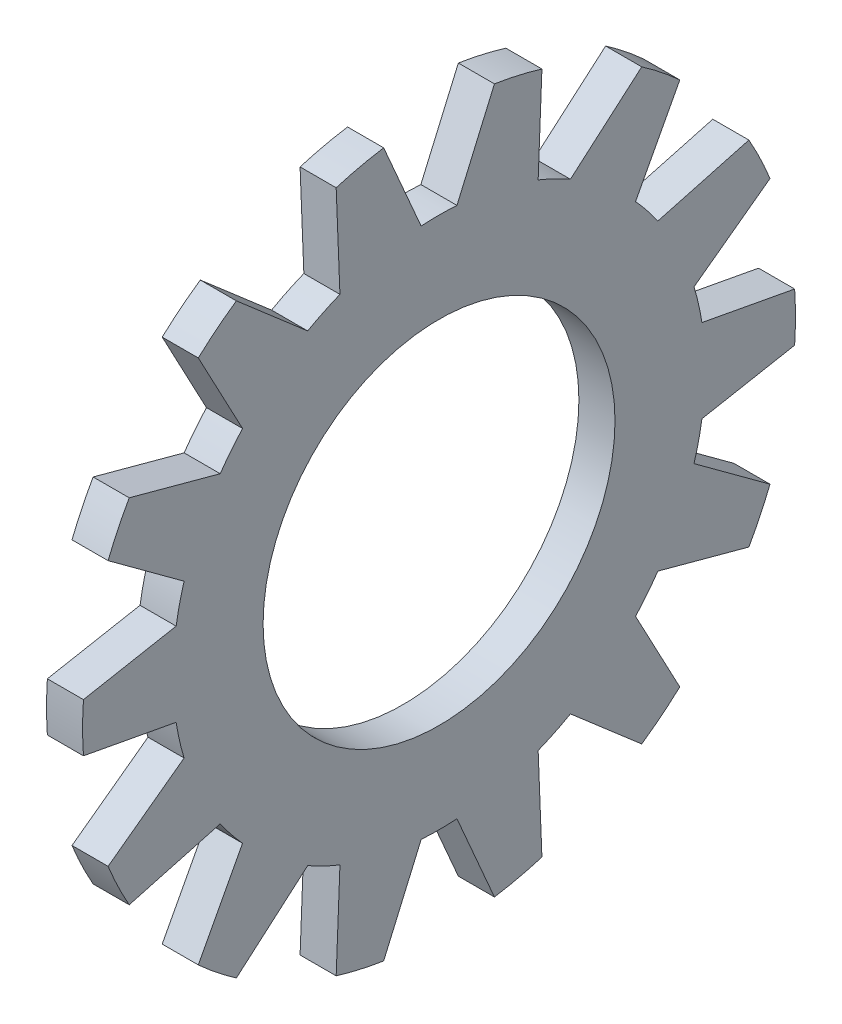
SolidWorks part; units mm, degrees
material "AISI 316 Stainless Steel Sheet (SS)"
ref_plane "Plane1" through (0, 0, 0) normal (0, 0, 1) x (1, 0, 0)
ref_plane "Plane2" through (0, 0, 0) normal (0, 1, 0) x (1, 0, 0)
ref_plane "Plane3" through (0, 0, 0) normal (1, 0, 0) x (0, 0, -1)
sketch "SecSke" plane through (0, 0, 0) normal (0, 0, 1) x (1, 0, 0)
  line L0 (-34.925, 0) -> (9.525, 0) construction
  line L1 (0, 2.4765) -> (0, 5.0165)
  line L2 (0, 5.0165) -> (-0.508, 5.0165)
  line L3 (-0.508, 5.0165) -> (-0.508, 2.4765)
  line L4 (-0.508, 2.4765) -> (0, 2.4765)
  dimension "Thickness" = 0.508
  dimension "Inside_dia" = 4.953
  dimension "Outside_dia" = 10.033
revolve "Body" add sketch "SecSke" angle 360 about L0
sketch "ExtCutSke" plane through (0, 0, 0) normal (1, 0, 0) x (0, 0, -1)
  line L0 (0, 0) -> (0, 5.2673) construction
  line L1 (-0.8823, 5.1929) -> (-0.252, 3.738)
  line L2 (0.8823, 5.1929) -> (0.252, 3.738)
  arc A0 (0.8823, 5.1929) -> (-0.8823, 5.1929) centre (0, 0) ccw
  arc A1 (0.252, 3.738) -> (-0.252, 3.738) centre (0, 0) ccw
  dimension "Cut_dia" = 7.493
  dimension "Clr_dia" = 10.5347
  dimension "Cut_ang" = 7.714
  dimension "Clr_ang" = 19.286
extrude "ExtCut" cut sketch "ExtCutSke" against normal through all
pattern_circular "ExtCuts" count 14 every 25.714 about axis through (-34.925, 0, 0) along (1, 0, 0) of "ExtCut"
equation "' \"Inside_dia@SecSke\" = 16"
equation "' \"Outside_dia@SecSke\" = 26"
equation "' \"Thickness@SecSke\" = 1.2"
equation "' \"Count@ExtCuts\" = 14"
equation "' \"Inside_dia@SecSke\" = 10.5"
equation "' \"Outside_dia@SecSke\" = 18"
equation "' \"Thickness@SecSke\" = 0.9"
equation "' \"Count@ExtCuts\" = 12"
equation "' \"Inside_dia@SecSke\" = 6.4"
equation "' \"Outside_dia@SecSke\" = 11"
equation "' \"Thickness@SecSke\" = 0.6"
equation "' \"Inside_dia@SecSke\" = 4.3"
equation "' \"Outside_dia@SecSke\" = 8.5"
equation "' \"Thickness@SecSke\" = 0.45"
equation "' \"Count@ExtCuts\" = 9"
equation "\"Angle@ExtCuts\" = 360 / \"Count@ExtCuts\""
equation "\"Clr_dia@ExtCutSke\" =  \"Outside_dia@SecSke\" * 1.05"
equation "\"Cut_dia@ExtCutSke\" = \"Outside_dia@SecSke\" - (\"Outside_dia@SecSke\"  - \"Inside_dia@SecSke\" ) * 0.5"
equation "\"Clr_ang@ExtCutSke\" = (360 / \"Count@ExtCuts\") * 0.75"
equation "\"Cut_ang@ExtCutSke\" = (360 / \"Count@ExtCuts\") * 0.3"
